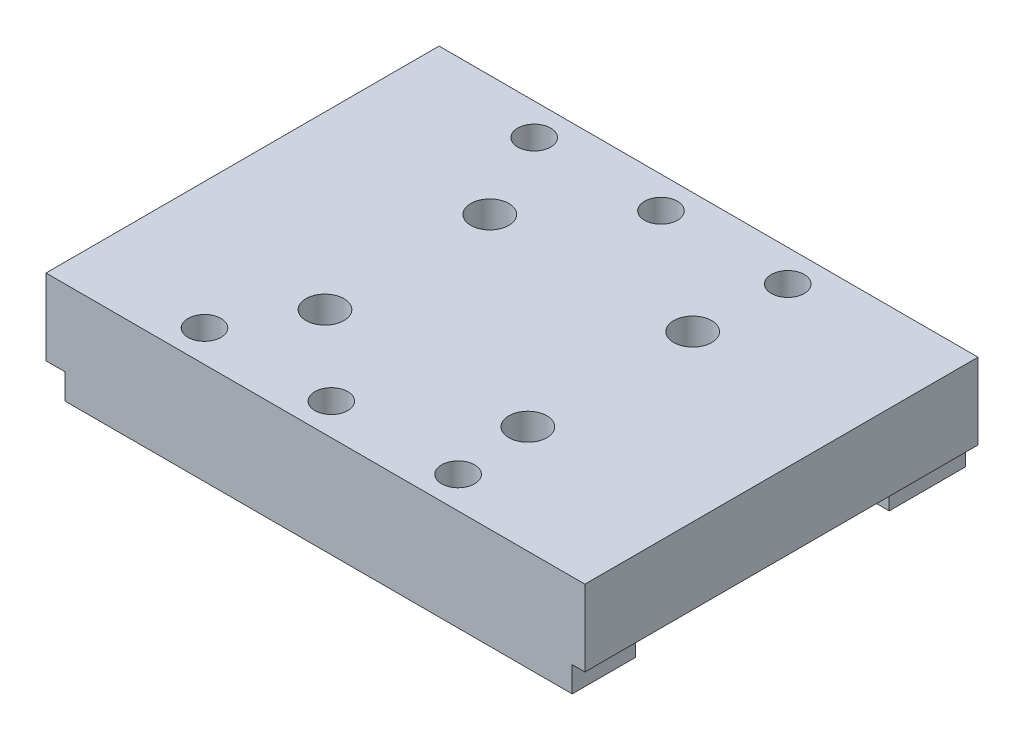
SolidWorks part; units mm, degrees
material "ABS"
ref_plane "前基準面" through (0, 0, 0) normal (0, 0, 1) x (1, 0, 0)
ref_plane "上基準面" through (0, 0, 0) normal (0, 1, 0) x (1, 0, 0)
ref_plane "右基準面" through (0, 0, 0) normal (1, 0, 0) x (0, 0, -1)
sketch "草圖1" plane through (0, 0, 0) normal (0, 1, 0) x (1, 0, 0)
  line L1 (0, 0) -> (40, 0)
  line L2 (0, 0) -> (0, 20)
  line L3 (0, 20) -> (40, 20)
  line L4 (40, 0) -> (40, 20)
  dimension "D1" = 20
  dimension "D2" = 40
extrude "填料-伸長1" add sketch "草圖1" along normal blind 3
sketch "草圖2" plane through (0, 3, 0) normal (0, 1, 0) x (1, 0, 0)
  line L1 (0, 0) -> (40, 0) construction
  line L3 (0, 20) -> (0, 0) construction
  circle A0 centre (28, 16.5) radius 1.5
  circle A1 centre (12, 16.5) radius 1.5
  circle A2 centre (12, 3.5) radius 1.5
  circle A3 centre (28, 3.5) radius 1.5
  dimension "D1" = 13
  dimension "D2" = 13
  dimension "D3" = 3.5
  dimension "D4" = 3.5
  dimension "D5" = 16
  dimension "D6" = 12
  dimension "D7" = 16
  dimension "D8" = 12
extrude "除料-伸長1" cut sketch "草圖2" against normal blind 3
sketch "草圖3" plane through (0, 0, 0) normal (0, 0, 1) x (1, 0, 0)
  line L0 (0, 0) -> (40, 0) construction
  line L1 (0, 3) -> (40, 3)
  line L2 (0, 3) -> (0, -5)
  line L3 (0, -5) -> (40, -5)
  line L4 (40, 3) -> (40, -5)
  dimension "D1" = 5
  dimension "D2" = 40
extrude "填料-伸長2" add sketch "草圖3" along normal blind 5
sketch "草圖4" plane through (0, 0, -20) normal (0, 0, -1) x (-1, 0, 0)
  line L0 (-40, 0) -> (0, 0) construction
  line L1 (-40, 3) -> (0, 3)
  line L2 (-40, 3) -> (-40, -5)
  line L3 (-40, -5) -> (0, -5)
  line L4 (0, 3) -> (0, -5)
  dimension "D1" = 5
  dimension "D2" = 40
extrude "填料-伸長3" add sketch "草圖4" along normal blind 6
sketch "草圖6" plane through (0, 3, 0) normal (0, 1, 0) x (1, 0, 0)
  line L0 (0, 26) -> (0, -5) construction
  line L1 (0, 26) -> (40, 26) construction
  line L2 (40, -5) -> (0, -5) construction
  circle A0 centre (8.5, 23.5) radius 1.3
  circle A1 centre (18.5, 23.5) radius 1.3
  circle A2 centre (28.5, 23.5) radius 1.3
  circle A3 centre (8.5, -2.5) radius 1.3
  circle A4 centre (18.5, -2.5) radius 1.3
  circle A5 centre (28.5, -2.5) radius 1.3
  dimension "D1" = 2.6
  dimension "D2" = 2.6
  dimension "D3" = 2.6
  dimension "D4" = 10
  dimension "D5" = 2.6
  dimension "D6" = 2.6
  dimension "2.6" = 2.6
  dimension "D7" = 10
  dimension "D8" = 10
  dimension "D9" = 10
  dimension "D10" = 8.5
  dimension "D11" = 2.5
  dimension "D12" = 2.5
  dimension "D13" = 2.5
  dimension "D14" = 8.5
  dimension "D15" = 2.5
  dimension "D16" = 2.5
  dimension "D17" = 2.5
extrude "除料-伸長2" cut sketch "草圖6" against normal blind 8
sketch "草圖11" plane through (0, 0, 5) normal (0, 0, 1) x (1, 0, 0)
  line L0 (0, 3) -> (-1.5, 3)
  line L1 (-1.5, 3) -> (-1.5, -3)
  line L2 (-1.5, -3) -> (0, -3)
  line L3 (0, 3) -> (0, -5) construction
  line L4 (0, -3) -> (0, 3)
  dimension "D1" = 1.5
  dimension "D2" = 6
extrude "填料-伸長5" add sketch "草圖11" against normal blind 31
sketch "草圖12" plane through (40, 0, 0) normal (1, 0, 0) x (0, 0, -1)
  line L0 (26, 3) -> (26, -5) construction
  line L1 (-5, 3) -> (26, 3)
  line L2 (-5, 3) -> (-5, -3)
  line L3 (-5, -3) -> (26, -3)
  line L4 (26, 3) -> (26, -3)
  dimension "D1" = 6
extrude "填料-伸長6" add sketch "草圖12" along normal blind 1
